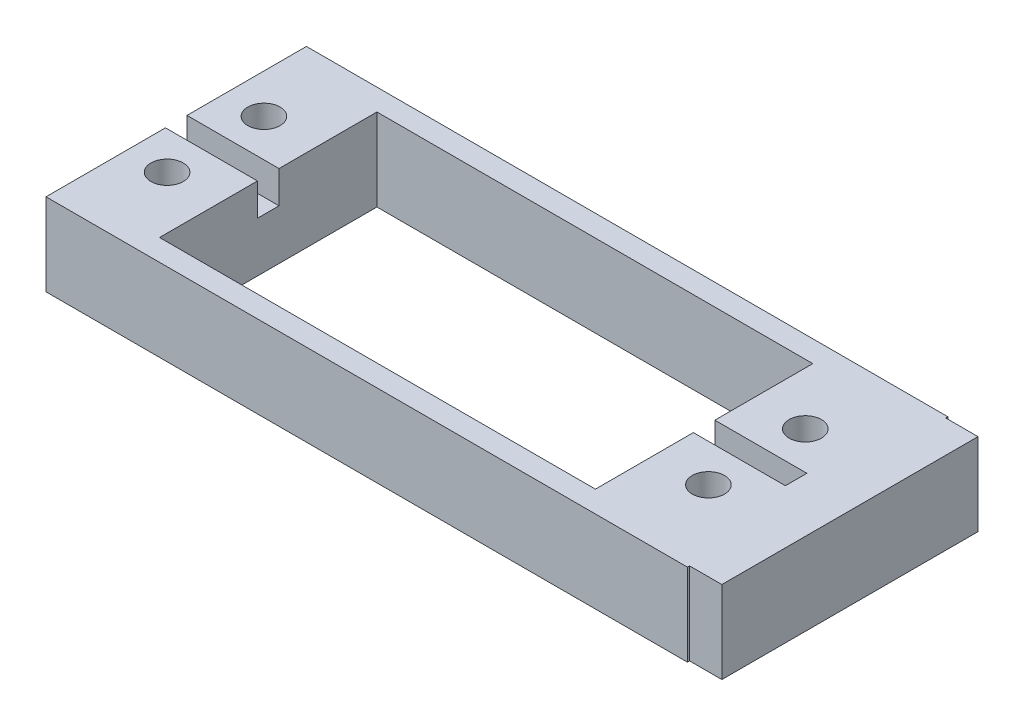
SolidWorks part; units mm, degrees
ref_plane "Front Plane" through (0, 0, 0) normal (0, 0, 1) x (1, 0, 0)
ref_plane "Top Plane" through (0, 0, 0) normal (0, 1, 0) x (1, 0, 0)
ref_plane "Right Plane" through (0, 0, 0) normal (1, 0, 0) x (0, 0, -1)
sketch "Sketch1" plane through (0, 0, 0) normal (0, 1, 0) x (1, 0, 0)
  line L0 (-101.8128, 12.4518) -> (-101.8128, 18.4813)
  line L1 (-101.8128, 21.4518) -> (-101.8128, 24.8665)
  line L2 (-94.5628, 5.4665) -> (-101.2128, 5.4665)
  line L3 (-95.1628, 6.0665) -> (-95.1628, 14.7945)
  line L4 (-54.8628, 14.7945) -> (-54.8628, 6.0665)
  line L5 (-48.2128, 18.4813) -> (-48.2128, 12.4518)
  line L6 (-85.1628, 25.4665) -> (-61.0205, 25.4665)
  line L7 (-95.2628, 25.4665) -> (-95.2628, 5.4665)
  line L8 (-101.8128, 25.4665) -> (-48.2128, 25.4665)
  line L9 (-101.8128, 25.4665) -> (-101.8128, 5.4665)
  line L10 (-101.8128, 5.4665) -> (-48.2128, 5.4665)
  line L11 (-48.2128, 25.4665) -> (-48.2128, 5.4665)
  line L12 (-95.1628, 25.4665) -> (-54.8628, 25.4665)
  line L13 (-95.1628, 25.4665) -> (-95.1628, 5.4665)
  line L14 (-95.1628, 5.4665) -> (-54.8628, 5.4665)
  line L15 (-54.8628, 25.4665) -> (-54.8628, 5.4665)
  line L17 (-54.7628, 25.4665) -> (-54.7628, 5.4665)
  line L19 (-95.2628, 25.5665) -> (-54.7628, 25.5665) construction
  line L20 (-95.2628, 5.3665) -> (-54.7628, 5.3665) construction
  line L22 (-95.2628, 25.5665) -> (-95.2628, 5.3665) construction
  line L23 (-54.7628, 25.5665) -> (-54.7628, 5.3665) construction
  circle A4 centre (-100.1628, 19.9665) radius 1.5
  circle A5 centre (-100.1628, 10.9665) radius 1.5
  circle A6 centre (-49.8628, 19.9665) radius 1.5
  circle A7 centre (-49.8628, 10.9665) radius 1.5
  dimension "D1" = 0.1
extrude "Boss-Extrude1" add sketch "Sketch1" along normal blind 7.8 contours L8 L17 L10 L11 L5 A7 A6 | L9 L10 L2 L7 L8 L1 L0 A5 A4
sketch "Sketch2" plane through (0, 7.8, 0) normal (0, 1, 0) x (1, 0, 0)
  line L5 (-101.8128, 25.4665) -> (-103.8128, 25.4665)
  line L6 (-101.8128, 25.4665) -> (-101.8128, 5.4665)
  line L7 (-101.8128, 5.4665) -> (-103.8128, 5.4665)
  line L8 (-101.8128, 25.4665) -> (-101.8128, 5.4665)
  line L9 (-101.8128, 5.4665) -> (-95.2628, 5.4665)
  line L10 (-95.2628, 5.4665) -> (-95.2628, 25.4665)
  line L11 (-95.2628, 25.4665) -> (-101.8128, 25.4665)
  line L12 (-101.8128, 25.4665) -> (-101.8128, 5.4665)
  line L13 (-101.8128, 5.4665) -> (-95.2628, 5.4665)
  line L14 (-95.2628, 5.4665) -> (-95.2628, 25.4665)
  line L15 (-95.2628, 25.4665) -> (-101.8128, 25.4665)
  line L16 (-103.8128, 25.4665) -> (-103.8128, 5.4665)
  line L17 (-48.2128, 25.4665) -> (-46.2128, 25.4665)
  line L18 (-48.2128, 25.4665) -> (-48.2128, 5.4665)
  line L19 (-48.2128, 5.4665) -> (-46.2128, 5.4665)
  line L20 (-46.2128, 25.4665) -> (-46.2128, 5.4665)
  line M11 (-48.2128, 5.4665) -> (-48.2128, 25.4665)
  dimension "D1" = 0
extrude "Boss-Extrude2" add sketch "Sketch2" against normal blind 7.8 contours L20 L17 L19 M11 | L5 L16 L7 L6
sketch "Sketch3" plane through (0, 7.8, 0) normal (0, 1, 0) x (1, 0, 0)
  line L0 (-54.7628, 25.4665) -> (-46.2128, 25.4665) construction
  line L1 (-95.2628, 25.4665) -> (-54.7628, 25.4665)
  line L2 (-95.2628, 25.4665) -> (-95.2628, 25.5665)
  line L3 (-95.2628, 25.5665) -> (-54.7628, 25.5665)
  line L4 (-54.7628, 25.4665) -> (-54.7628, 25.5665)
  line L5 (-95.2628, 5.4665) -> (-54.7628, 5.4665)
  line L6 (-95.2628, 5.4665) -> (-95.2628, 5.3665)
  line L7 (-95.2628, 5.3665) -> (-54.7628, 5.3665)
  line L8 (-54.7628, 5.4665) -> (-54.7628, 5.3665)
  line L9 (-103.8128, 25.4665) -> (-95.2628, 25.4665)
  line L10 (-103.8128, 25.4665) -> (-103.8128, 25.5665)
  line L11 (-103.8128, 25.5665) -> (-95.2628, 25.5665)
  line L12 (-95.2628, 25.4665) -> (-95.2628, 25.5665)
  line L13 (-54.7628, 25.5665) -> (-46.2128, 25.5665)
  line L14 (-54.7628, 25.5665) -> (-54.7628, 25.4665)
  line L15 (-54.7628, 25.4665) -> (-46.2128, 25.4665)
  line L16 (-46.2128, 25.5665) -> (-46.2128, 25.4665)
  line L17 (-103.8128, 5.4665) -> (-95.2628, 5.4665) construction
  line L18 (-103.8128, 5.4665) -> (-46.2128, 5.4665)
  line L19 (-103.8128, 5.4665) -> (-103.8128, 5.3665)
  line L20 (-103.8128, 5.3665) -> (-46.2128, 5.3665)
  line L21 (-46.2128, 5.4665) -> (-46.2128, 5.3665)
  line L22 (-103.8128, 25.4665) -> (-103.8128, 5.4665) construction
  line M5 (-95.2628, 25.4665) -> (-103.8128, 25.4665)
  line M7 (-103.8128, 5.4665) -> (-95.2628, 5.4665)
extrude "Boss-Extrude3" add sketch "Sketch3" against normal blind 7.8 contours L19 L20 L6 M7 | L11 L10 L2 M5 | L16 L13 L4 L15 | L21 L18 L8 L20
sketch "Sketch4" plane through (0, 7.8, 0) normal (0, 1, 0) x (1, 0, 0)
  line L1 (-103.8128, 25.5665) -> (-46.2128, 25.5665)
  line L2 (-103.8128, 25.5665) -> (-103.8128, 27.5665)
  line L3 (-103.8128, 27.5665) -> (-46.2128, 27.5665)
  line L4 (-46.2128, 25.5665) -> (-46.2128, 27.5665)
  line L5 (-103.8128, 5.3665) -> (-46.2128, 5.3665)
  line L6 (-103.8128, 5.3665) -> (-103.8128, 3.3665)
  line L7 (-103.8128, 3.3665) -> (-46.2128, 3.3665)
  line L8 (-46.2128, 5.3665) -> (-46.2128, 3.3665)
extrude "Boss-Extrude4" add sketch "Sketch4" against normal blind 7.8
sketch "Sketch5" plane through (0, 7.8, 0) normal (0, 1, 0) x (1, 0, 0)
  line L0 (-95.2628, 14.4665) -> (-103.8128, 16.4665) construction
  line L1 (-95.2628, 16.4665) -> (-103.8128, 14.4665) construction
  line L3 (-46.2128, 27.5665) -> (-46.2128, 3.3665) construction
  line L4 (-75.0128, 15.4665) -> (-75.0128, 20.7139)
  line L5 (-54.7628, 16.4665) -> (-46.2128, 16.4665)
  line L6 (-54.7628, 16.4665) -> (-54.7628, 14.4665)
  line L7 (-54.7628, 14.4665) -> (-46.2128, 14.4665)
  line L8 (-46.2128, 16.4665) -> (-46.2128, 14.4665)
  line L9 (-54.7628, 16.4665) -> (-46.2128, 14.4665) construction
  line L10 (-54.7628, 14.4665) -> (-46.2128, 16.4665) construction
  line L11 (-103.8128, 16.4665) -> (-103.8128, 14.4665)
  line L12 (-95.2628, 14.4665) -> (-103.8128, 14.4665)
  line L13 (-95.2628, 16.4665) -> (-95.2628, 14.4665)
  line L14 (-95.2628, 16.4665) -> (-103.8128, 16.4665)
  point P6 (-99.5378, 15.4665)
  point P10 (-50.4878, 15.4665)
  line M4 (-46.2128, 3.3665) -> (-46.2128, 27.5665)
  line M6 (-103.8128, 27.5665) -> (-103.8128, 3.3665)
  line M9 (-54.7628, 25.5665) -> (-54.7628, 5.3665)
  line M11 (-95.2628, 5.3665) -> (-95.2628, 25.5665)
extrude "Cut-Extrude1" cut sketch "Sketch5" against normal blind 3 contours L14 L12 M11 M6 | L7 L5 M9 M4
sketch "Sketch6" plane through (0, 7.8, 0) normal (0, 1, 0) x (1, 0, 0)
  line L0 (-82.1628, 15.4665) -> (-88.1628, 15.4665)
  line L1 (-95.2628, 15.4665) -> (-85.1628, 15.4665)
  line L2 (-95.2628, 14.4665) -> (-95.2628, 16.4665) construction
  line L3 (-97.661, -0.0334) -> (-97.661, 30.9666)
  line L4 (-72.661, -0.0334) -> (-72.661, 30.9666)
  line L5 (-93.161, -4.5334) -> (-77.161, -4.5334)
  line L6 (-93.161, 35.4666) -> (-77.161, 35.4666)
  line L7 (-103.8128, 16.4665) -> (-95.2628, 16.4665) construction
  line L8 (-95.2628, 16.4665) -> (-95.2628, 25.5665) construction
  line L9 (-95.2628, 25.5665) -> (-54.7628, 25.5665) construction
  line L10 (-54.7628, 25.5665) -> (-54.7628, 16.4665) construction
  line L11 (-54.7628, 16.4665) -> (-46.2128, 16.4665) construction
  line L12 (-46.2128, 16.4665) -> (-46.2128, 27.5665) construction
  line L13 (-46.2128, 27.5665) -> (-103.8128, 27.5665) construction
  line L14 (-103.8128, 27.5665) -> (-103.8128, 16.4665) construction
  line L15 (-95.2628, 5.3665) -> (-95.2628, 14.4665) construction
  line L16 (-95.2628, 14.4665) -> (-103.8128, 14.4665) construction
  line L17 (-103.8128, 14.4665) -> (-103.8128, 3.3665) construction
  line L18 (-103.8128, 3.3665) -> (-46.2128, 3.3665) construction
  line L19 (-46.2128, 3.3665) -> (-46.2128, 14.4665) construction
  line L20 (-46.2128, 14.4665) -> (-54.7628, 14.4665) construction
  line L21 (-54.7628, 14.4665) -> (-54.7628, 5.3665) construction
  line L22 (-54.7628, 5.3665) -> (-95.2628, 5.3665) construction
  line L23 (-103.8128, 16.4665) -> (-95.2628, 16.4665)
  line L24 (-95.2628, 16.4665) -> (-95.2628, 25.5665)
  line L25 (-95.2628, 25.5665) -> (-54.7628, 25.5665)
  line L26 (-54.7628, 25.5665) -> (-54.7628, 16.4665)
  line L27 (-54.7628, 16.4665) -> (-46.2128, 16.4665)
  line L28 (-46.2128, 16.4665) -> (-46.2128, 27.5665)
  line L29 (-46.2128, 27.5665) -> (-103.8128, 27.5665)
  line L30 (-103.8128, 27.5665) -> (-103.8128, 16.4665)
  line L31 (-95.2628, 5.3665) -> (-95.2628, 14.4665)
  line L32 (-95.2628, 14.4665) -> (-103.8128, 14.4665)
  line L33 (-103.8128, 14.4665) -> (-103.8128, 3.3665)
  line L34 (-103.8128, 3.3665) -> (-46.2128, 3.3665)
  line L35 (-46.2128, 3.3665) -> (-46.2128, 14.4665)
  line L36 (-46.2128, 14.4665) -> (-54.7628, 14.4665)
  line L37 (-54.7628, 14.4665) -> (-54.7628, 5.3665)
  line L38 (-54.7628, 5.3665) -> (-95.2628, 5.3665)
  circle A0 centre (-77.161, 30.9666) radius 1.5
  circle A1 centre (-93.161, 30.9666) radius 1.5
  circle A2 centre (-77.161, -0.0334) radius 1.5
  circle A3 centre (-93.161, -0.0334) radius 1.5
  circle A4 centre (-85.1628, 15.4665) radius 3
  circle A5 centre (-77.161, -0.0334) radius 4.5
  circle A6 centre (-93.161, -0.0334) radius 4.5
  circle A7 centre (-93.161, 30.9666) radius 4.5
  circle A8 centre (-77.161, 30.9666) radius 4.5
  line M9 (-46.2128, 27.5665) -> (-103.8128, 27.5665)
  dimension "D1" = 3
extrude "Boss-Extrude5" add sketch "Sketch6" against normal up to surface (7.8 mm away) contours A6 L34 L3 | A6 L34 A3 | A6 L5 A5 L34 | A5 L34 A2 | A5 L4 L34 | L29 A8 A0 | A8 L4 M9 | A8 L6 A7 M9 | L29 A7 A1 | A7 L3 M9 up to face at (-75.0128, 0, -15.4665)
sketch "Sketch7" plane through (0, 7.8, 0) normal (0, 1, 0) x (1, 0, 0)
  line L1 (-97.661, 27.5665) -> (-72.661, 27.5665)
  line L2 (-97.661, 27.5665) -> (-97.661, 3.3665)
  line L3 (-97.661, 3.3665) -> (-72.661, 3.3665)
  line L4 (-72.661, 27.5665) -> (-72.661, 3.3665)
  line L28 (-103.8128, 16.4665) -> (-95.2628, 16.4665)
  line L29 (-95.2628, 16.4665) -> (-95.2628, 25.5665)
  line L30 (-95.2628, 25.5665) -> (-54.7628, 25.5665)
  line L31 (-54.7628, 25.5665) -> (-54.7628, 16.4665)
  line L32 (-54.7628, 16.4665) -> (-46.2128, 16.4665)
  line L33 (-46.2128, 16.4665) -> (-46.2128, 27.5665)
  line L34 (-46.2128, 27.5665) -> (-72.661, 27.5665)
  line L35 (-72.661, 27.5665) -> (-72.661, 30.9666)
  line L36 (-77.161, 35.4666) -> (-93.161, 35.4666)
  line L37 (-97.661, 30.9666) -> (-97.661, 27.5665)
  line L38 (-97.661, 27.5665) -> (-103.8128, 27.5665)
  line L39 (-103.8128, 27.5665) -> (-103.8128, 16.4665)
  line L40 (-103.8128, 16.4665) -> (-95.2628, 16.4665)
  line L41 (-95.2628, 16.4665) -> (-95.2628, 25.5665)
  line L42 (-95.2628, 25.5665) -> (-54.7628, 25.5665)
  line L43 (-54.7628, 25.5665) -> (-54.7628, 16.4665)
  line L44 (-54.7628, 16.4665) -> (-46.2128, 16.4665)
  line L45 (-46.2128, 16.4665) -> (-46.2128, 27.5665)
  line L46 (-46.2128, 27.5665) -> (-72.661, 27.5665)
  line L47 (-72.661, 27.5665) -> (-72.661, 30.9666)
  line L48 (-77.161, 35.4666) -> (-93.161, 35.4666)
  line L49 (-97.661, 30.9666) -> (-97.661, 27.5665)
  line L50 (-97.661, 27.5665) -> (-103.8128, 27.5665)
  line L51 (-103.8128, 27.5665) -> (-103.8128, 16.4665)
  line L52 (-95.2628, 5.3665) -> (-95.2628, 14.4665)
  line L53 (-95.2628, 14.4665) -> (-103.8128, 14.4665)
  line L54 (-103.8128, 14.4665) -> (-103.8128, 3.3665)
  line L55 (-103.8128, 3.3665) -> (-97.661, 3.3665)
  line L56 (-97.661, 3.3665) -> (-97.661, -0.0334)
  line L57 (-93.161, -4.5334) -> (-77.161, -4.5334)
  line L58 (-72.661, -0.0334) -> (-72.661, 3.3665)
  line L59 (-72.661, 3.3665) -> (-46.2128, 3.3665)
  line L60 (-46.2128, 3.3665) -> (-46.2128, 14.4665)
  line L61 (-46.2128, 14.4665) -> (-54.7628, 14.4665)
  line L62 (-54.7628, 14.4665) -> (-54.7628, 5.3665)
  line L63 (-54.7628, 5.3665) -> (-95.2628, 5.3665)
  line L64 (-95.2628, 5.3665) -> (-95.2628, 14.4665)
  line L65 (-95.2628, 14.4665) -> (-103.8128, 14.4665)
  line L66 (-103.8128, 14.4665) -> (-103.8128, 3.3665)
  line L67 (-103.8128, 3.3665) -> (-97.661, 3.3665)
  line L68 (-97.661, 3.3665) -> (-97.661, -0.0334)
  line L69 (-93.161, -4.5334) -> (-77.161, -4.5334)
  line L70 (-72.661, -0.0334) -> (-72.661, 3.3665)
  line L71 (-72.661, 3.3665) -> (-46.2128, 3.3665)
  line L72 (-46.2128, 3.3665) -> (-46.2128, 14.4665)
  line L73 (-46.2128, 14.4665) -> (-54.7628, 14.4665)
  line L74 (-54.7628, 14.4665) -> (-54.7628, 5.3665)
  line L75 (-54.7628, 5.3665) -> (-95.2628, 5.3665)
  arc A4 (-72.661, 30.9666) -> (-77.161, 35.4666) centre (-77.161, 30.9666) ccw
  arc A5 (-93.161, 35.4666) -> (-97.661, 30.9666) centre (-93.161, 30.9666) ccw
  arc A6 (-72.661, 30.9666) -> (-77.161, 35.4666) centre (-77.161, 30.9666) ccw
  arc A7 (-93.161, 35.4666) -> (-97.661, 30.9666) centre (-93.161, 30.9666) ccw
  arc A8 (-97.661, -0.0334) -> (-93.161, -4.5334) centre (-93.161, -0.0334) ccw
  arc A9 (-77.161, -4.5334) -> (-72.661, -0.0334) centre (-77.161, -0.0334) ccw
  arc A10 (-97.661, -0.0334) -> (-93.161, -4.5334) centre (-93.161, -0.0334) ccw
  arc A11 (-77.161, -4.5334) -> (-72.661, -0.0334) centre (-77.161, -0.0334) ccw
  line M35 (-97.661, 3.3665) -> (-97.661, -0.0334)
  arc M36 (-97.661, -0.0334) -> (-93.161, -4.5334) centre (-93.161, -0.0334) ccw
  line M37 (-93.161, -4.5334) -> (-77.161, -4.5334)
  arc M38 (-77.161, -4.5334) -> (-72.661, -0.0334) centre (-77.161, -0.0334) ccw
  line M39 (-72.661, -0.0334) -> (-72.661, 3.3665)
  circle M45 centre (-93.161, -0.0334) radius 1.5
  circle M46 centre (-77.161, -0.0334) radius 1.5
  dimension "D1" = 0
  dimension "D2" = 0
extrude "Cut-Extrude2" cut sketch "Sketch7" against normal blind 4 contours L3 M35 M36 M37 M38 M39 M46 M45 | L48 A7 L49 L1 L47 A6
sketch "Sketch8" plane through (-46.2128, 0, 0) normal (1, 0, 0) x (0, 0, -1)
  line L1 (3.3665, 7.8) -> (27.5665, 7.8)
  line L2 (3.3665, 7.8) -> (3.3665, 0)
  line L3 (3.3665, 0) -> (27.5665, 0)
  line L4 (27.5665, 7.8) -> (27.5665, 0)
extrude "Boss-Extrude6" add sketch "Sketch8" along normal blind 5
sketch "Sketch10" plane through (0, 0, 0) normal (0, -1, 0) x (1, 0, 0)
  line L1 (-103.8128, -3.3665) -> (-41.2128, -3.3665)
  line L2 (-103.8128, -3.3665) -> (-103.8128, -27.5665)
  line L3 (-103.8128, -27.5665) -> (-41.2128, -27.5665)
  line L4 (-41.2128, -3.3665) -> (-41.2128, -27.5665)
  line L12 (-41.2128, -27.5665) -> (-41.2128, -3.3665)
  line L13 (-41.2128, -3.3665) -> (-72.661, -3.3665)
  line L14 (-72.661, -3.3665) -> (-72.661, 0.0334)
  line L15 (-77.161, 4.5334) -> (-93.161, 4.5334)
  line L16 (-97.661, 0.0334) -> (-97.661, -3.3665)
  line L17 (-97.661, -3.3665) -> (-103.8128, -3.3665)
  line L18 (-103.8128, -3.3665) -> (-103.8128, -27.5665)
  line L19 (-103.8128, -27.5665) -> (-97.661, -27.5665)
  line L20 (-97.661, -27.5665) -> (-97.661, -30.9666)
  line L21 (-93.161, -35.4666) -> (-77.161, -35.4666)
  line L22 (-72.661, -30.9666) -> (-72.661, -27.5665)
  line L23 (-72.661, -27.5665) -> (-41.2128, -27.5665)
  line L25 (-41.2128, -3.3665) -> (-72.661, -3.3665)
  line L26 (-72.661, -3.3665) -> (-72.661, 0.0334)
  line L27 (-77.161, 4.5334) -> (-93.161, 4.5334)
  line L28 (-97.661, 0.0334) -> (-97.661, -3.3665)
  line L29 (-97.661, -3.3665) -> (-103.8128, -3.3665)
  line L30 (-103.8128, -3.3665) -> (-103.8128, -27.5665)
  line L31 (-103.8128, -27.5665) -> (-97.661, -27.5665)
  line L32 (-97.661, -27.5665) -> (-97.661, -30.9666)
  line L33 (-93.161, -35.4666) -> (-77.161, -35.4666)
  line L34 (-72.661, -30.9666) -> (-72.661, -27.5665)
  line L35 (-72.661, -27.5665) -> (-41.2128, -27.5665)
  line L40 (-41.2128, -27.5665) -> (-41.2128, -3.3665)
  arc A4 (-72.661, 0.0334) -> (-77.161, 4.5334) centre (-77.161, 0.0334) ccw
  arc A5 (-93.161, 4.5334) -> (-97.661, 0.0334) centre (-93.161, 0.0334) ccw
  arc A6 (-97.661, -30.9666) -> (-93.161, -35.4666) centre (-93.161, -30.9666) ccw
  arc A7 (-77.161, -35.4666) -> (-72.661, -30.9666) centre (-77.161, -30.9666) ccw
  arc A8 (-72.661, 0.0334) -> (-77.161, 4.5334) centre (-77.161, 0.0334) ccw
  arc A9 (-93.161, 4.5334) -> (-97.661, 0.0334) centre (-93.161, 0.0334) ccw
  arc A10 (-97.661, -30.9666) -> (-93.161, -35.4666) centre (-93.161, -30.9666) ccw
  arc A11 (-77.161, -35.4666) -> (-72.661, -30.9666) centre (-77.161, -30.9666) ccw
  circle M17 centre (-93.161, -30.9666) radius 1.5
  circle M18 centre (-77.161, -30.9666) radius 1.5
  circle M19 centre (-93.161, 0.0334) radius 1.5
  circle M20 centre (-77.161, 0.0334) radius 1.5
  line M31 (-72.661, -3.3665) -> (-72.661, 0.0334)
  arc M32 (-72.661, 0.0334) -> (-77.161, 4.5334) centre (-77.161, 0.0334) ccw
  line M33 (-77.161, 4.5334) -> (-93.161, 4.5334)
  arc M34 (-93.161, 4.5334) -> (-97.661, 0.0334) centre (-93.161, 0.0334) ccw
  line M35 (-97.661, 0.0334) -> (-97.661, -3.3665)
  line M39 (-97.661, -27.5665) -> (-97.661, -30.9666)
  arc M40 (-97.661, -30.9666) -> (-93.161, -35.4666) centre (-93.161, -30.9666) ccw
  line M41 (-93.161, -35.4666) -> (-77.161, -35.4666)
  arc M42 (-77.161, -35.4666) -> (-72.661, -30.9666) centre (-77.161, -30.9666) ccw
  line M43 (-72.661, -30.9666) -> (-72.661, -27.5665)
  dimension "D1" = 0
extrude "Cut-Extrude3" cut sketch "Sketch10" against normal through all contours L1 M35 M31 M32 M33 M34 M19 M20 | L3 M39 M40 M41 M42 M43 M18 M17
sketch "Sketch14" plane through (0, 0, 0) normal (0, -1, 0) x (1, 0, 0)
  line L0 (-41.2128, -27.5665) -> (-103.8128, -27.5665) construction
  line L1 (-41.2128, -3.3665) -> (-44.2128, -3.3665)
  line L3 (-41.2128, -27.5665) -> (-44.2128, -27.5665)
  line L4 (-44.2128, -3.3665) -> (-44.2128, -27.5665)
  line L5 (-41.2128, -3.3665) -> (-41.2128, -27.5665) construction
  line L6 (-44.2128, -3.3665) -> (-41.2128, -3.3665)
  line L7 (-44.2128, -3.3665) -> (-44.2128, -3.5665)
  line L8 (-44.2128, -3.5665) -> (-41.2128, -3.5665)
  line L9 (-41.2128, -3.3665) -> (-41.2128, -3.5665)
  line L10 (-44.2128, -27.5665) -> (-41.2128, -27.5665)
  line L11 (-44.2128, -27.5665) -> (-44.2128, -27.3665)
  line L12 (-44.2128, -27.3665) -> (-41.2128, -27.3665)
  line L13 (-41.2128, -27.5665) -> (-41.2128, -27.3665)
  line M11 (-41.2128, -27.5665) -> (-41.2128, -3.3665)
  line M12 (-41.2128, -3.3665) -> (-103.8128, -3.3665)
  line M14 (-103.8128, -27.5665) -> (-41.2128, -27.5665)
extrude "Cut-Extrude5" cut sketch "Sketch14" against normal blind 13.8 contours L4 L8 M11 M12 | L12 L4 M14 M11
sketch "Sketch15" plane through (0, 0, 0) normal (0, -1, 0) x (1, 0, 0)
  line L8 (-41.2128, -3.5665) -> (-44.2128, -3.5665)
  line L9 (-44.2128, -3.5665) -> (-44.2128, -3.3665)
  line L10 (-44.2128, -3.3665) -> (-103.8128, -3.3665)
  line L11 (-103.8128, -3.3665) -> (-103.8128, -27.5665)
  line L12 (-103.8128, -27.5665) -> (-44.2128, -27.5665)
  line L13 (-44.2128, -27.5665) -> (-44.2128, -27.3665)
  line L14 (-44.2128, -27.3665) -> (-41.2128, -27.3665)
  line L15 (-41.2128, -27.3665) -> (-41.2128, -3.5665)
  line L16 (-41.2128, -3.5665) -> (-44.2128, -3.5665)
  line L17 (-44.2128, -3.5665) -> (-44.2128, -3.3665)
  line L18 (-44.2128, -3.3665) -> (-103.8128, -3.3665)
  line L19 (-103.8128, -3.3665) -> (-103.8128, -27.5665)
  line L20 (-103.8128, -27.5665) -> (-44.2128, -27.5665)
  line L21 (-44.2128, -27.5665) -> (-44.2128, -27.3665)
  line L22 (-44.2128, -27.3665) -> (-41.2128, -27.3665)
  line L23 (-41.2128, -27.3665) -> (-41.2128, -3.5665)
  dimension "D1" = 0
extrude "Cut-Extrude6" cut sketch "Sketch15" against normal blind 0.15
